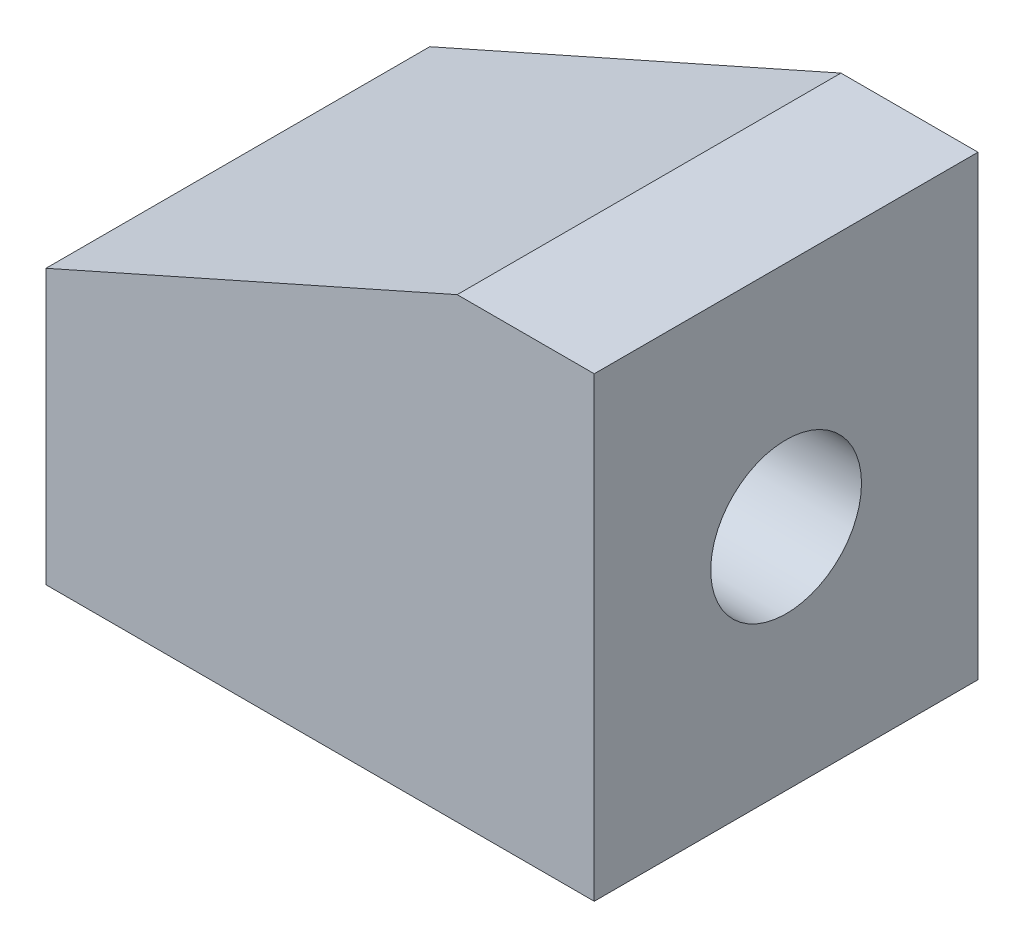
SolidWorks part; units mm, degrees
ref_plane "Piano frontale" through (0, 0, 0) normal (0, 0, 1) x (1, 0, 0)
ref_plane "Piano superiore" through (0, 0, 0) normal (0, 1, 0) x (1, 0, 0)
ref_plane "Piano destro" through (0, 0, 0) normal (1, 0, 0) x (0, 0, -1)
sketch "Schizzo1" plane through (0, 0, 0) normal (0, 0, 1) x (1, 0, 0)
  line L0 (30, 0) -> (30, 50)
  line L1 (30, 50) -> (15, 50)
  line L2 (15, 50) -> (-30, 30)
  line L3 (-30, 30) -> (-30, 0)
  line L4 (-30, 0) -> (30, 0)
  dimension "D1" = 30
  dimension "D2" = 60
  dimension "D3" = 50
  dimension "D4" = 15
extrude "Estrusione-Estrusione1" add sketch "Schizzo1" along normal mid plane 42
sketch "Schizzo2" plane through (30, 0, 0) normal (1, 0, 0) x (0, 0, -1)
  line L0 (-21, 0) -> (21, 0) construction
  circle A0 centre (0, 25) radius 9.7445
  point P4 (0, 0)
  dimension "D1" = 25
hole_wizard "Foro filettato M18x1.5-1" positions "Schizzo3" profile "Schizzo5" tap size "M18x1.5" standard "IS"
sketch "Schizzo3" plane through (30, 0, 0) normal (1, 0, 0) x (0, 0, -1)
  point P0 (0, 25)
sketch "Schizzo5" plane through (30, 25, 0) normal (0, 1, 0) x (0, 0, -1)
  line L0 (0, 0) -> (0, 43.5)
  line L1 (0, 43.5) -> (8.25, 38.5429)
  line L2 (8.25, 38.5429) -> (8.25, 0)
  line L5 (8.25, 0) -> (0, 0)
  line L10 (0, 43.5) -> (-8.25, 38.5429) construction
  line L11 (0, -6.35) -> (0, 107.95) construction
  dimension "Tap Drill Dia." = 16.5
  dimension "Tap Drill Depth" = 43.5
  dimension "Drill Angle" = 118
cosmetic thread "Filettatura del foro1" parameters "D1"=36, "D2"=18
